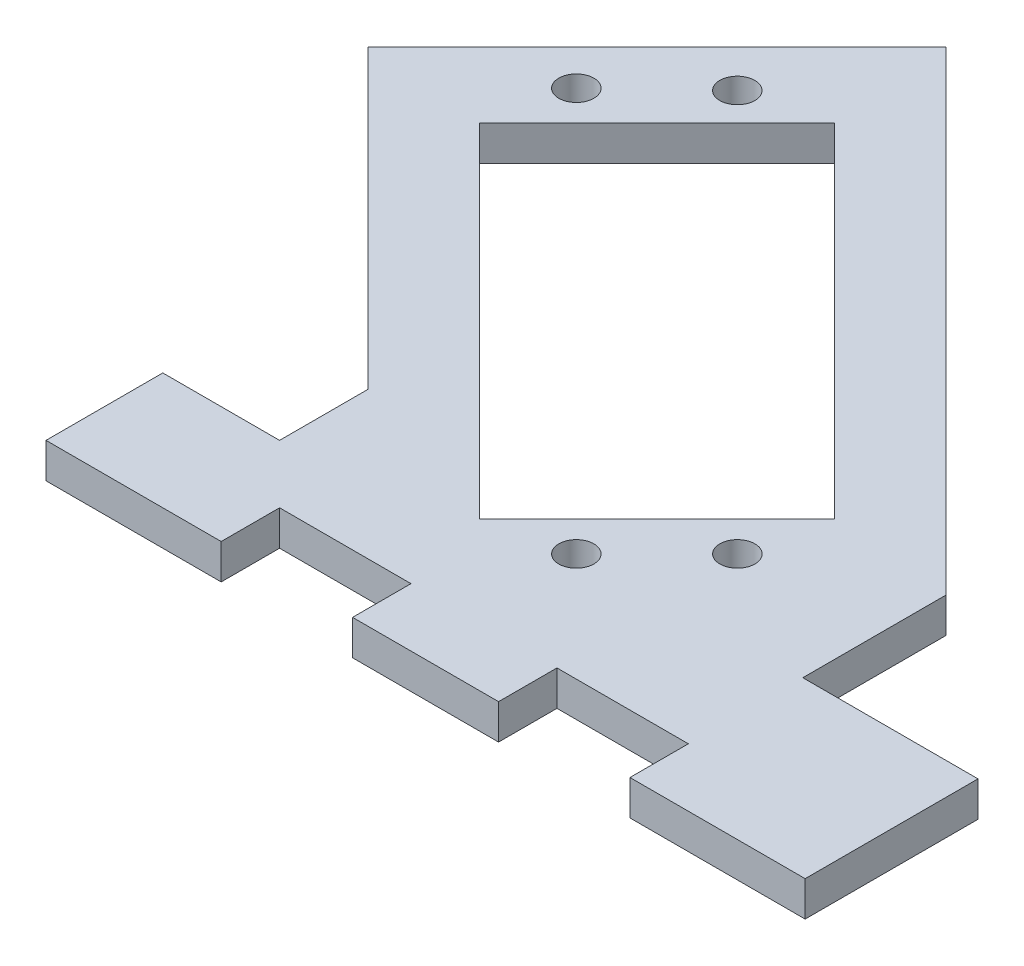
SolidWorks part; units mm, degrees
ref_plane "前视基准面" through (0, 0, 0) normal (0, 0, 1) x (1, 0, 0)
ref_plane "上视基准面" through (0, 0, 0) normal (0, 1, 0) x (1, 0, 0)
ref_plane "右视基准面" through (0, 0, 0) normal (1, 0, 0) x (0, 0, -1)
sketch "草图1" plane through (0, 0, 0) normal (0, 1, 0) x (1, 0, 0)
  line L0 (0, 0) -> (-31244.4874, 0) construction
  line L1 (0, 0) -> (0, -31244.4874) construction
  line L2 (0, 0) -> (15.2028, 15.2028)
  line L3 (15.2028, 15.2028) -> (-14.1421, 44.5477)
  line L4 (-14.1421, 44.5477) -> (-29.3449, 29.3449)
  line L5 (-29.3449, 29.3449) -> (0, 0)
  line L8 (-14.376, 4.8301) -> (-14.376, -2.7224)
  line L9 (-14.376, -2.7224) -> (-24.376, -2.7224)
  line L10 (-24.376, -2.7224) -> (-24.376, -12.7224)
  line L11 (-24.376, -12.7224) -> (-9.376, -12.7224)
  line L12 (-9.376, -12.7224) -> (-9.376, -7.7224)
  line L13 (-9.376, -7.7224) -> (1.874, -7.7224)
  line L14 (1.874, -7.7224) -> (1.874, -12.7224)
  line L15 (1.874, -12.7224) -> (14.374, -12.7224)
  line L16 (14.374, -12.7224) -> (14.374, -7.7224)
  line L17 (14.374, -7.7224) -> (25.624, -7.7224)
  line L18 (25.624, -7.7224) -> (25.624, -12.7224)
  line L19 (25.624, -12.7224) -> (40.624, -12.7224)
  line L20 (40.624, -12.7224) -> (40.624, 2.0776)
  line L23 (25.624, 2.0776) -> (40.624, 2.0776)
  line L24 (-14.376, 4.8301) -> (-39.7748, 30.2288)
  line L25 (-39.7748, 30.2288) -> (-15.026, 54.9776)
  line L26 (-15.026, 54.9776) -> (25.624, 14.3276)
  line L28 (25.624, 14.3276) -> (25.624, 2.0776)
  line L29 (-51.0885, 66.2913) -> (7.6014, 7.6014) construction
  line L30 (-14.6725, 14.6725) -> (35340.6666, 35370.0115) construction
  circle A0 centre (-27.7846, 36.0931) radius 1.5
  circle A1 centre (-20.7249, 42.818) radius 1.5
  circle A2 centre (6.7482, 1.5603) radius 1.5
  circle A3 centre (13.6425, 8.4546) radius 1.5
  point P38 (-21.7435, 36.9463)
  point P40 (-14.6725, 14.6725)
  point P41 (0.5303, 29.8753)
  dimension "D20" = 3
  dimension "D21" = 3
  dimension "D2" = 65
  dimension "D3" = 5
  dimension "D4" = 5
  dimension "D5" = 10
  dimension "D6" = 10
  dimension "D7" = 12.5
  dimension "D8" = 11.25
  dimension "D9" = 15
  dimension "D10" = 14.8
  dimension "D11" = 12.25
  dimension "D12" = 41.5
  dimension "D13" = 21.5
  dimension "D14" = 45
  dimension "D15" = 15
  dimension "D16" = 35
  dimension "D17" = 67.7
  dimension "D18" = 6.75
  dimension "D19" = 8
  dimension "D22" = 9.75
  dimension "D23" = 9.75
  dimension "D24" = 48.6
extrude "凸台-拉伸1" add sketch "草图1" along normal blind 3
